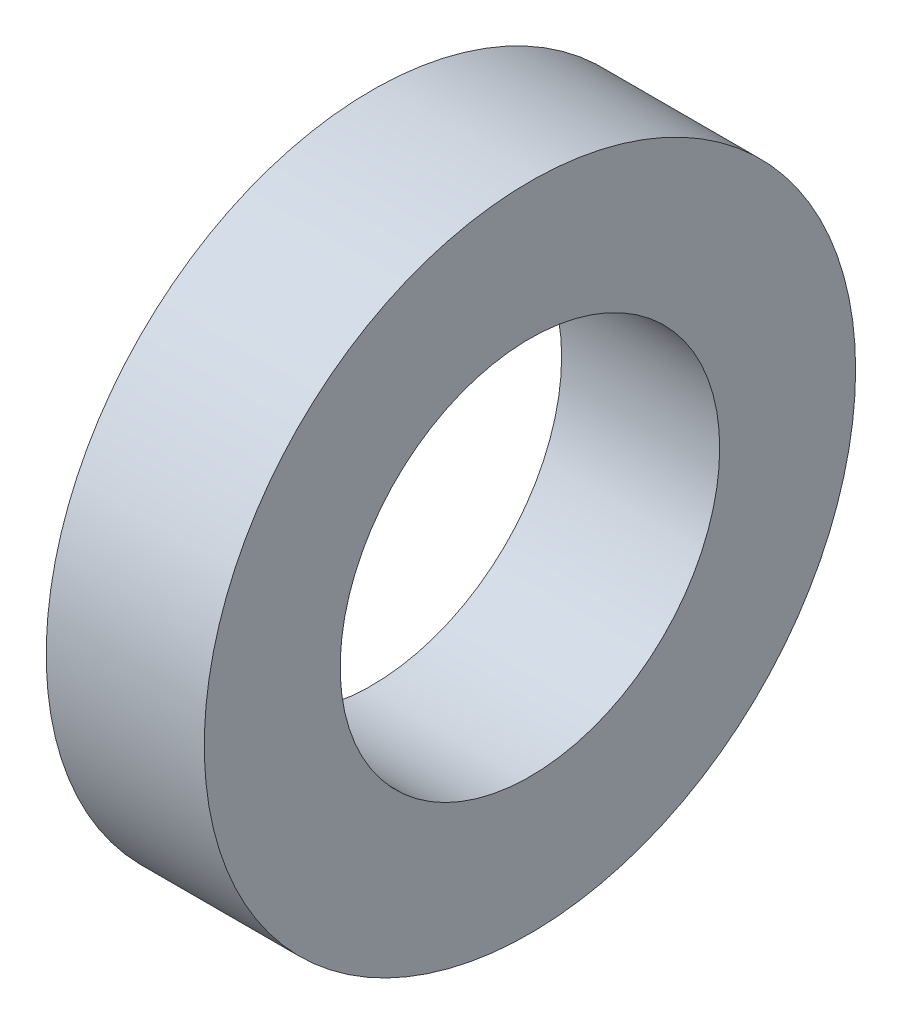
SolidWorks part; units mm, degrees
material "6061-T6 (SS)"
ref_plane "Front Plane" through (0, 0, 0) normal (0, 0, 1) x (1, 0, 0)
ref_plane "Top Plane" through (0, 0, 0) normal (0, 1, 0) x (1, 0, 0)
ref_plane "Right Plane" through (0, 0, 0) normal (1, 0, 0) x (0, 0, -1)
sketch "Sketch1" plane through (0, 0, 0) normal (1, 0, 0) x (0, 0, -1)
  line L1 (4.7625, -2.7496) -> (4.7625, 2.7496) construction
  line L2 (4.7625, 2.7496) -> (0, 5.4993) construction
  line L3 (0, 5.4993) -> (-4.7625, 2.7496) construction
  line L4 (-4.7625, 2.7496) -> (-4.7625, -2.7496) construction
  line L5 (-4.7625, -2.7496) -> (0, -5.4993) construction
  line L6 (0, -5.4993) -> (4.7625, -2.7496) construction
  circle A0 centre (0, 0) radius 4.7625 construction
  circle A1 centre (0, 0) radius 5.5501
  circle A2 centre (0, 0) radius 9.525
  point P11 (2.7496, 4.7625)
  point P12 (2.7496, 4.7625)
  point P13 (0, 0)
  dimension "D1" = 9.525
  dimension "D2" = 19.05
  dimension "D3" = 0.0508
extrude "Boss-Extrude1" add sketch "Sketch1" along normal blind 4.6228
